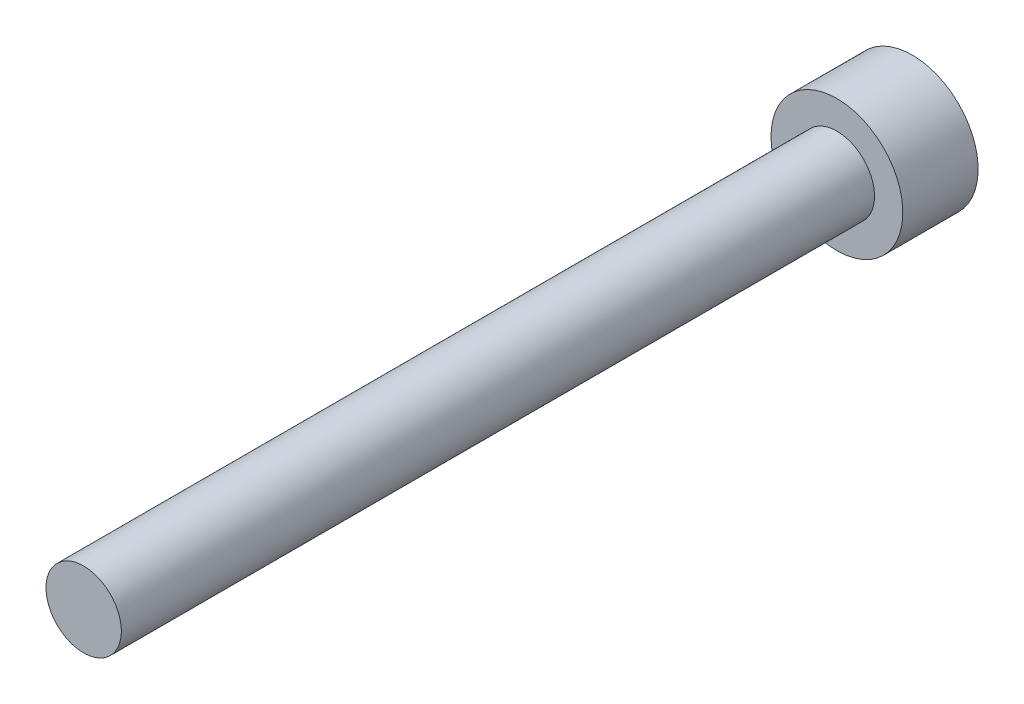
SolidWorks part; units mm, degrees
material "AISI Type 316L stainless steel"
ref_plane "Front Plane" through (0, 0, 0) normal (0, 0, 1) x (1, 0, 0)
ref_plane "Top Plane" through (0, 0, 0) normal (0, 1, 0) x (1, 0, 0)
ref_plane "Right Plane" through (0, 0, 0) normal (1, 0, 0) x (0, 0, -1)
sketch "Sketch1" plane through (0, 0, 0) normal (0, 1, 0) x (1, 0, 0)
  line L0 (0, 0) -> (2, 0)
  line L1 (2, 0) -> (2, 40)
  line L2 (2, 40) -> (3.5, 40)
  line L3 (3.5, 40) -> (3.5, 44)
  line L4 (3.5, 44) -> (0, 44)
  line L5 (0, 44) -> (0, 0)
  dimension "D1" = 2
  dimension "D2" = 3.5
  dimension "D3" = 4
  dimension "D4" = 40
revolve "Revolve1" add sketch "Sketch1" angle 360 about L5
sketch "Sketch2" plane through (0, 0, -44) normal (0, 0, -1) x (-1, 0, 0)
  line L0 (0, 0) -> (-0.866, -1.5) construction
  line L1 (-0.866, -1.5) -> (0.866, -1.5)
  line L2 (0.866, -1.5) -> (0, 0) construction
  line L3 (-1.7321, 0) -> (-0.866, -1.5)
  line L4 (-0.866, 1.5) -> (-1.7321, 0)
  line L5 (0.866, 1.5) -> (-0.866, 1.5)
  line L6 (1.7321, 0) -> (0.866, 1.5)
  line L7 (0.866, -1.5) -> (1.7321, 0)
  point P16 (0, 0)
  dimension "D1" = 1.5
  dimension "D2" = 6
extrude "Cut-Extrude1" cut sketch "Sketch2" against normal blind 3
